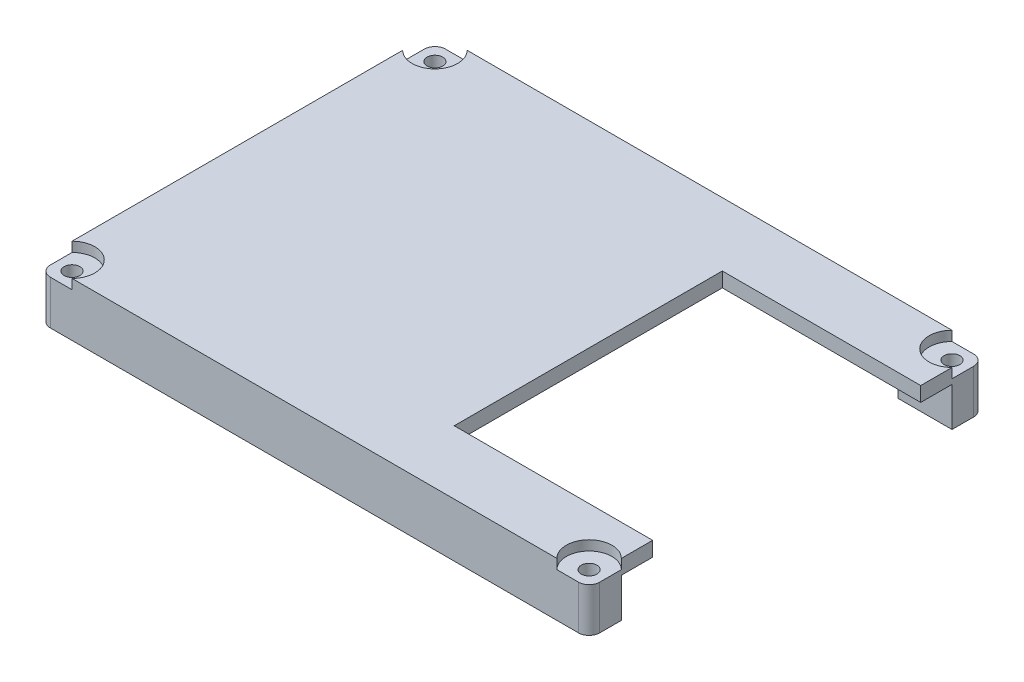
SolidWorks part; units mm, degrees
ref_plane "前视基准面" through (0, 0, 0) normal (0, 0, 1) x (1, 0, 0)
ref_plane "上视基准面" through (0, 0, 0) normal (0, 1, 0) x (1, 0, 0)
ref_plane "右视基准面" through (0, 0, 0) normal (1, 0, 0) x (0, 0, -1)
sketch "草图1" plane through (0, 0, 0) normal (0, 1, 0) x (1, 0, 0)
  line L0 (-13.122, 19.5292) -> (-7.622, 19.5292)
  line L1 (-7.622, 19.5292) -> (-7.622, 22.8292)
  line L2 (-7.622, 22.8292) -> (-63.832, 22.8292)
  line L3 (-63.832, 22.8292) -> (-63.832, -17.6008)
  line L4 (-63.832, -17.6008) -> (-7.622, -17.6008)
  line L5 (-7.622, -17.6008) -> (-7.622, -14.3008)
  line L6 (-7.622, -14.3008) -> (-13.122, -14.3008)
  line L7 (-13.122, -14.3008) -> (-13.122, -16.1008)
  line L8 (-13.122, -16.1008) -> (-60.332, -16.1008)
  line L9 (-60.332, -16.1008) -> (-60.332, -14.3008)
  line L10 (-60.332, -14.3008) -> (-62.332, -14.3008)
  line L11 (-62.332, -14.3008) -> (-62.332, 19.5292)
  line L12 (-62.332, 19.5292) -> (-60.332, 19.5292)
  line L13 (-60.332, 19.5292) -> (-60.332, 21.3292)
  line L14 (-60.332, 21.3292) -> (-13.122, 21.3292)
  line L15 (-13.122, 21.3292) -> (-13.122, 19.5292)
  dimension "D1" = 40.43
extrude "凸台-拉伸1" add sketch "草图1" along normal blind 4
sketch "草图2" plane through (0, 4, 0) normal (0, 1, 0) x (1, 0, 0)
  line L0 (-63.832, -17.6008) -> (-7.622, -17.6008) construction
  line L1 (-63.832, 22.8292) -> (-62.332, 22.8292)
  line L2 (-63.832, 22.8292) -> (-63.832, -17.6008)
  line L3 (-63.832, -17.6008) -> (-62.332, -17.6008)
  line L4 (-62.332, 22.8292) -> (-62.332, -17.6008)
  line L5 (-63.082, -17.6008) -> (-63.082, 22.8292) construction
  line L6 (-63.832, 2.6142) -> (-62.332, 2.6142) construction
  point P312 (-63.082, 2.6142)
extrude "凸台-拉伸2" add sketch "草图2" along normal blind 1.5
sketch "草图3" plane through (-62.332, 0, 0) normal (1, 0, 0) x (0, 0, -1)
  line L0 (22.8292, 5.5) -> (22.8292, 4) construction
  line L1 (22.8292, 5.5) -> (-17.6008, 5.5)
  line L2 (22.8292, 5.5) -> (22.8292, 4)
  line L3 (22.8292, 4) -> (-17.6008, 4)
  line L4 (-17.6008, 5.5) -> (-17.6008, 4)
  line L5 (2.6142, 4) -> (2.6142, 5.5) construction
  line L6 (22.8292, 4.75) -> (-17.6008, 4.75) construction
  line L7 (-17.6008, 5.5) -> (22.8292, 5.5) construction
  point P428 (2.6142, 4.75)
extrude "凸台-拉伸5" add sketch "草图3" along normal up to surface (54.71 mm away) up to face at (-7.622, 2, -21.1792)
sketch "草图4" plane through (-7.622, 0, 0) normal (1, 0, 0) x (0, 0, -1)
  line L0 (-17.6008, 5.5) -> (-17.6008, 0) construction
  line L1 (22.8292, 5.5) -> (-17.6008, 5.5)
  line L2 (22.8292, 5.5) -> (22.8292, 4)
  line L3 (22.8292, 4) -> (-17.6008, 4)
  line L4 (-17.6008, 5.5) -> (-17.6008, 4)
  line L5 (2.6142, 4) -> (2.6142, 5.5) construction
  line L6 (22.8292, 4.75) -> (-17.6008, 4.75) construction
  point P152 (2.6142, 4.75)
extrude "切除-拉伸1" cut sketch "草图4" against normal blind 20.3
sketch "草图5" plane through (-27.922, 0, 0) normal (1, 0, 0) x (0, 0, -1)
  line L0 (21.3292, 4) -> (-16.1008, 4) construction
  line L1 (-17.6008, 5.5) -> (-11.1008, 5.5)
  line L2 (-17.6008, 5.5) -> (-17.6008, 4)
  line L3 (-17.6008, 4) -> (-11.1008, 4)
  line L4 (-11.1008, 5.5) -> (-11.1008, 4)
  line L5 (-14.3508, 4) -> (-14.3508, 5.5) construction
  line L6 (-17.6008, 4.75) -> (-11.1008, 4.75) construction
  line L7 (22.8292, 5.5) -> (-17.6008, 5.5) construction
  line L8 (22.8292, 4) -> (16.3292, 4)
  line L9 (22.8292, 4) -> (22.8292, 5.5)
  line L10 (22.8292, 5.5) -> (16.3292, 5.5)
  line L11 (16.3292, 4) -> (16.3292, 5.5)
  line L12 (19.5792, 5.5) -> (19.5792, 4) construction
  line L13 (22.8292, 4.75) -> (16.3292, 4.75) construction
  point P82 (19.5792, 4.75)
  point P92 (-14.3508, 4.75)
  dimension "D1" = 6.5
  dimension "D2" = 6.5
extrude "凸台-拉伸6" add sketch "草图5" along normal blind 20.3
sketch "草图6" plane through (0, 0, 0) normal (0, -1, 0) x (1, 0, 0)
  line L0 (-63.832, -2.6142) -> (-62.332, -2.6142)
  line L2 (-63.832, -22.8292) -> (-63.832, 17.6008) construction
  line L3 (-62.332, 14.3008) -> (-62.332, -19.5292) construction
  line L4 (-35.727, -22.8292) -> (-35.727, -21.3292)
  line L5 (-7.622, -22.8292) -> (-63.832, -22.8292) construction
  line L6 (-60.332, -21.3292) -> (-13.122, -21.3292) construction
  circle A0 centre (-62.182, -21.1792) radius 0.8
  circle A1 centre (-62.182, 15.9508) radius 0.8
  circle A2 centre (-9.272, 15.9508) radius 0.8
  circle A3 centre (-9.272, -21.1792) radius 0.8
  dimension "D3" = 1.6
extrude "切除-拉伸2" cut sketch "草图6" against normal blind 20.3 contours A3 | A2 | A1 | A0
sketch "草图7" plane through (0, 5.5, 0) normal (0, 1, 0) x (1, 0, 0)
  circle A0 centre (-62.182, -15.9508) radius 2.3335
  circle A1 centre (-62.182, 21.1792) radius 2.3335
  circle A2 centre (-9.272, 21.1792) radius 2.3335
  circle A3 centre (-9.272, -15.9508) radius 2.3335
extrude "切除-拉伸5" cut sketch "草图7" against normal blind 1
sketch "草图9" plane through (0, 0, 0) normal (0, -1, 0) x (1, 0, 0)
  line L1 (-63.832, -22.8292) -> (-63.832, 17.6008) construction
  line L2 (-7.622, -22.8292) -> (-63.832, -22.8292) construction
  line L3 (-62.7477, -22.8292) -> (-63.832, -22.8292)
  line L4 (-63.832, -21.7449) -> (-63.832, -22.8292)
  line L6 (-62.7477, 17.6008) -> (-63.832, 17.6008)
  line L7 (-63.832, 16.5165) -> (-63.832, 17.6008)
  line L9 (-7.622, 16.5165) -> (-7.622, 17.6008)
  line L10 (-8.7063, 17.6008) -> (-7.622, 17.6008)
  line L11 (-7.622, -21.7449) -> (-7.622, -22.8292)
  line L12 (-8.7063, -22.8292) -> (-7.622, -22.8292)
  circle A0 centre (-62.182, -21.1792) radius 0.8 construction
  arc A1 (-63.832, -21.7449) -> (-62.7477, -22.8292) centre (-62.7477, -21.7449) ccw
  arc A2 (-63.832, 16.5165) -> (-62.7477, 17.6008) centre (-62.7477, 16.5165) cw
  arc A3 (-7.622, 16.5165) -> (-8.7063, 17.6008) centre (-8.7063, 16.5165) ccw
  arc A4 (-7.622, -21.7449) -> (-8.7063, -22.8292) centre (-8.7063, -21.7449) cw
extrude "切除-拉伸6" cut sketch "草图9" against normal blind 10
